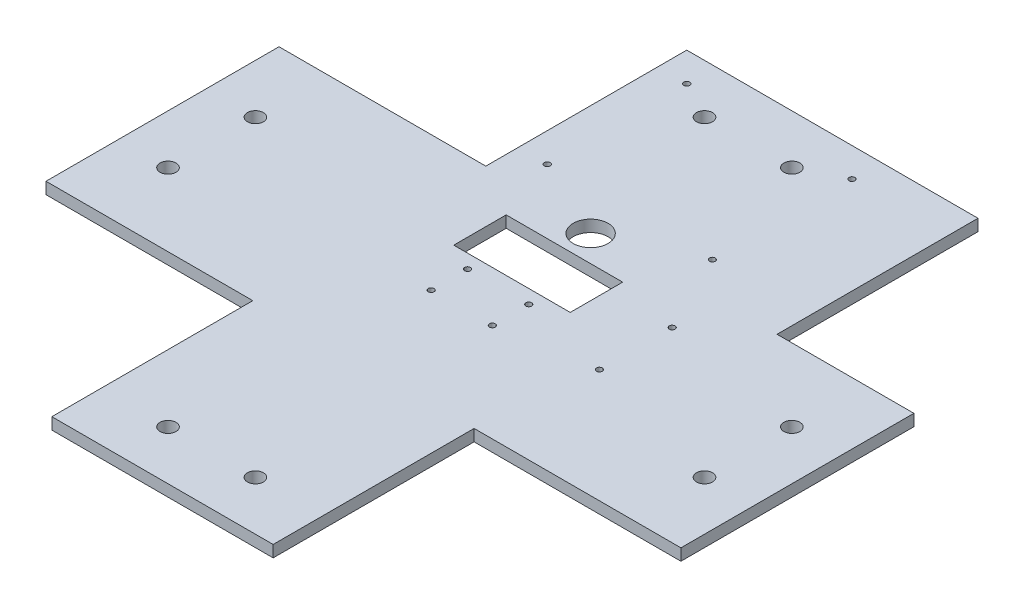
SolidWorks part; units mm, degrees
ref_plane "Front Plane" through (0, 0, 0) normal (0, 0, 1) x (1, 0, 0)
ref_plane "Top Plane" through (0, 0, 0) normal (0, 1, 0) x (1, 0, 0)
ref_plane "Right Plane" through (0, 0, 0) normal (1, 0, 0) x (0, 0, -1)
sketch "Sketch1" plane through (0, 0, 0) normal (0, 1, 0) x (1, 0, 0)
  line L1 (-50, 40) -> (50, 40)
  line L2 (-50, 40) -> (-50, -40)
  line L3 (-50, -40) -> (50, -40)
  line L4 (50, 40) -> (50, -40)
  line L5 (-50, 40) -> (50, -40) construction
  line L6 (-50, -40) -> (50, 40) construction
  point P0 (0, 0)
  dimension "D1" = 100
  dimension "D2" = 80
extrude "Boss-Extrude1" add sketch "Sketch1" along normal blind 4
sketch "Sketch2" plane through (0, 4, 0) normal (0, 1, 0) x (1, 0, 0)
  line L0 (-50, 40) -> (-50, -40) construction
  line L1 (-40, 30) -> (16.7, 30) construction
  line L2 (-40, 30) -> (-40, -17.9) construction
  line L3 (-40, -17.9) -> (16.7, -17.9) construction
  line L4 (16.7, 30) -> (16.7, -17.9) construction
  line L5 (50, 40) -> (-50, 40) construction
  circle A0 centre (-40, 30) radius 1
  circle A1 centre (16.7, 30) radius 1
  circle A2 centre (16.7, -17.9) radius 1
  circle A3 centre (-40, -17.9) radius 1
  dimension "D3" = 2
  dimension "D1" = 56.7
  dimension "D2" = 47.9
  dimension "D4" = 10
  dimension "D5" = 10
extrude "Cut-Extrude1" cut sketch "Sketch2" against normal through all
sketch "Sketch3" plane through (0, 4, 0) normal (0, 1, 0) x (1, 0, 0)
  line L0 (7.9935, -40) -> (50, -40)
  line L1 (-50, -40) -> (-32.0065, -40)
  line L2 (-50, -40) -> (-50, -80)
  line L3 (-50, -80) -> (50, -80)
  line L4 (50, -40) -> (50, -80)
  line L5 (50, -40) -> (50, 40) construction
  line L6 (-32.0065, -40) -> (-32.0065, -58)
  line L7 (-32.0065, -58) -> (7.9935, -58)
  line L8 (7.9935, -40) -> (7.9935, -58)
  dimension "D1" = 18
  dimension "D2" = 40
  dimension "D3" = 40
extrude "Boss-Extrude2" add sketch "Sketch3" against normal blind 4
sketch "Sketch4" plane through (0, 4, 0) normal (0, 1, 0) x (1, 0, 0)
  line L0 (-12.0065, -62.75) -> (-12.0065, -58) construction
  line L1 (-22.5065, -62.75) -> (-1.5065, -62.75) construction
  line L2 (-22.5065, -62.75) -> (-22.5065, -75.25) construction
  line L3 (-22.5065, -75.25) -> (-1.5065, -75.25) construction
  line L4 (-1.5065, -62.75) -> (-1.5065, -75.25) construction
  line L5 (7.9935, -58) -> (-32.0065, -58) construction
  line L6 (-32.0065, -58) -> (-32.0065, -80) construction
  line L7 (-50, -80) -> (50, -80) construction
  line L8 (-32.0065, -69) -> (-22.5065, -69) construction
  circle A0 centre (-22.5065, -62.75) radius 1
  circle A1 centre (-22.5065, -75.25) radius 1
  circle A2 centre (-1.5065, -75.25) radius 1
  circle A3 centre (-1.5065, -62.75) radius 1
  dimension "D3" = 2
  dimension "D1" = 21
  dimension "D2" = 12.5
extrude "Cut-Extrude2" cut sketch "Sketch4" against normal blind 4
sketch "Sketch5" plane through (0, 4, 0) normal (0, 1, 0) x (1, 0, 0)
  line L0 (30, -70) -> (30, -45) construction
  line L1 (-50, -80) -> (50, -80) construction
  line L2 (50, -80) -> (50, 40) construction
  circle A0 centre (30, -45) radius 1
  circle A1 centre (30, -70) radius 1
  circle A2 centre (-1.5065, -62.75) radius 1 construction
  dimension "D1" = 25
  dimension "D2" = 10
  dimension "D3" = 20
extrude "Cut-Extrude3" cut sketch "Sketch5" against normal blind 4
sketch "Sketch6" plane through (0, 4, 0) normal (0, 1, 0) x (1, 0, 0)
  line L0 (-12.0065, -40) -> (-12.0065, -50040) construction
  line L1 (-32.0065, -40) -> (7.9935, -40) construction
  circle A0 centre (-12.0065, -31) radius 6
  point P4 (-12.0065, -40)
  dimension "D1" = 12
  dimension "D2" = 9
extrude "Cut-Extrude4" cut sketch "Sketch6" against normal through all
sketch "Sketch7" plane through (0, 0, 0) normal (0, -1, 0) x (1, 0, 0)
  line L0 (-1.5065, 62.75) -> (-22.5065, 62.75) construction
  line L1 (-22.5065, 62.75) -> (-22.5065, 75.25) construction
  line L2 (-12.0065, 62.75) -> (-12.0065, 50062.75) construction
  line L3 (-22.5065, 69) -> (49977.4935, 69) construction
  line L4 (50, -40) -> (50, 69) construction
  line L5 (96.9935, 29) -> (50, 29)
  line L6 (96.9935, 29) -> (96.9935, 109)
  line L7 (96.9935, 109) -> (25.9869, 109)
  line L8 (-121.0065, 29) -> (-121.0065, 109)
  line L9 (50, 80) -> (50, -40) construction
  line L10 (-12.0065, 103.4736) -> (96.9935, 103.4736) construction
  line L11 (-50, -40) -> (-50, 80) construction
  line L12 (-50, -40) -> (-50, 80) construction
  line L13 (-50, 29) -> (-50, 80)
  line L14 (-50, 80) -> (50, 80)
  line L15 (50, 29) -> (50, 80)
  line L16 (-50, 29) -> (-121.0065, 29)
  line L17 (-50, 178) -> (25.9869, 178)
  line L18 (-50, 178) -> (-50, 109)
  line L20 (25.9869, 178) -> (25.9869, 109)
  line L21 (-50, 178) -> (25.9869, 109) construction
  line L22 (-50, 109) -> (25.9869, 178) construction
  line L23 (50, -40) -> (-50, -40) construction
  line L24 (-50, 109) -> (-121.0065, 109)
  point P8 (-12.0065, 62.75)
  point P11 (-22.5065, 69)
  point P30 (-12.0065, 143.5)
  dimension "D1" = 80
extrude "Boss-Extrude3" add sketch "Sketch7" against normal blind 4
sketch "Sketch8" plane through (0, 4, 0) normal (0, 1, 0) x (1, 0, 0)
  line L0 (-121.0065, -69) -> (49878.9935, -69) construction
  line L1 (-121.0065, -109) -> (-121.0065, -29) construction
  line L2 (-12.0065, -109) -> (-12.0065, 49891) construction
  line L4 (-13.8667, -70.8601) -> (-35369.2057, -35426.1992) construction
  line L5 (25.9869, -178) -> (-50, -178) construction
  circle A0 centre (-104.1065, -84) radius 2.75
  circle A1 centre (-104.1065, -54) radius 2.75
  circle A2 centre (80.0935, -54) radius 2.75
  circle A3 centre (80.0935, -84) radius 2.75
  circle A4 centre (-27.0065, 23.1) radius 2.75
  circle A5 centre (2.9935, 23.1) radius 2.75
  circle A6 centre (2.9935, -161.1) radius 2.75
  circle A7 centre (-27.0065, -161.1) radius 2.75
  point P4 (-121.0065, -69)
  point P7 (-12.0065, -178)
  point P20 (-12.0065, -69)
  dimension "D1" = 5.5
  dimension "D2" = 30
  dimension "D3" = 16.9
  dimension "D4" = 45
extrude "Cut-Extrude5" cut sketch "Sketch8" against normal through all
